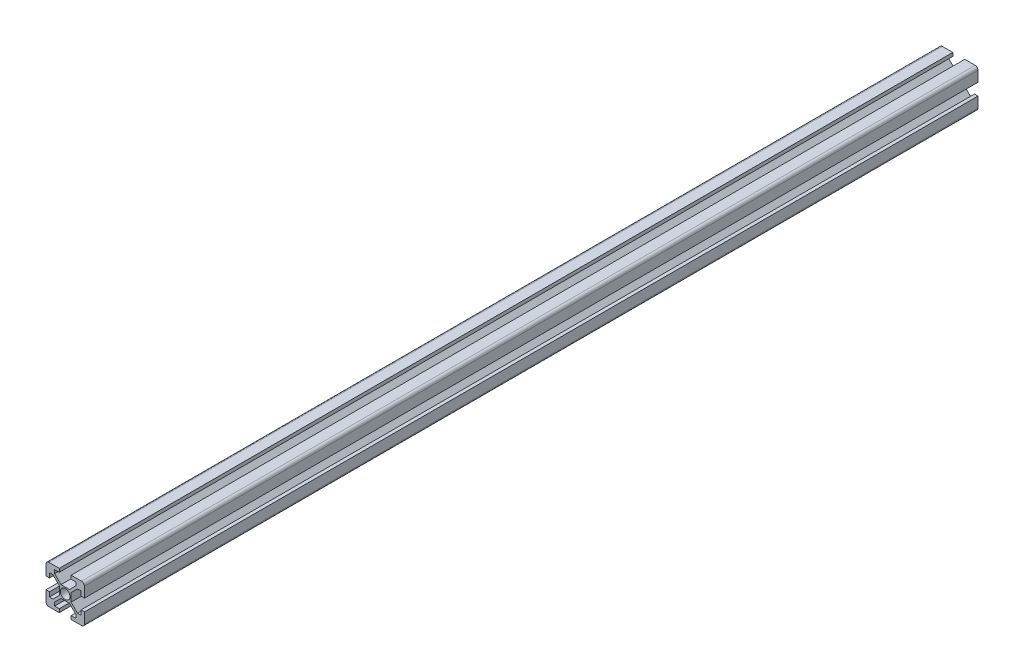
SolidWorks part; units mm, degrees
ref_plane "前视基准面" through (0, 0, 0) normal (0, 0, 1) x (1, 0, 0)
ref_plane "上视基准面" through (0, 0, 0) normal (0, 1, 0) x (1, 0, 0)
ref_plane "右视基准面" through (0, 0, 0) normal (1, 0, 0) x (0, 0, -1)
sketch "草图1" plane through (0, 0, 0) normal (0, 0, 1) x (1, 0, 0)
  line L0 (-10, -3.1) -> (-8.2, -3.1)
  line L1 (-8.5, 10) -> (8.5, 10)
  line L2 (-10, 8.5) -> (-10, -8.5)
  line L3 (-8.5, -10) -> (8.5, -10)
  line L4 (10, 8.5) -> (10, -8.5)
  line L5 (-10, 10) -> (10, -10) construction
  line L6 (-10, -10) -> (10, 10) construction
  line L7 (-3.0541, 3.1) -> (3.0541, 3.1)
  line L8 (-3.0541, 3.1) -> (-3.0541, -3.1)
  line L9 (-3.0541, -3.1) -> (3.0541, -3.1)
  line L10 (3.0541, 3.1) -> (3.0541, -3.1)
  line L11 (-3.0541, 3.1) -> (3.0541, -3.1) construction
  line L12 (-3.0541, -3.1) -> (3.0541, 3.1) construction
  line L13 (-8.2, -3.1) -> (-8.2, -5.5)
  line L14 (-8.2, -5.5) -> (-6.3971, -5.5)
  line L15 (-6.3971, -5.5) -> (-3.0541, -2.1571)
  line L16 (-5.5, 6.3971) -> (-2.1571, 3.0541)
  line L17 (-5.5, 8.2) -> (-5.5, 6.3971)
  line L18 (-3.1, 8.2) -> (-5.5, 8.2)
  line L19 (-3.1, 10) -> (-3.1, 8.2)
  line L20 (6.3971, 5.5) -> (3.0541, 2.1571)
  line L21 (8.2, 5.5) -> (6.3971, 5.5)
  line L22 (8.2, 3.1) -> (8.2, 5.5)
  line L23 (10, 3.1) -> (8.2, 3.1)
  line L24 (5.5, -6.3971) -> (2.1571, -3.0541)
  line L25 (5.5, -8.2) -> (5.5, -6.3971)
  line L26 (3.1, -8.2) -> (5.5, -8.2)
  line L27 (3.1, -10) -> (3.1, -8.2)
  line L28 (-3.1, -10) -> (-3.1, -8.2)
  line L29 (-3.1, -8.2) -> (-5.5, -8.2)
  line L30 (-5.5, -8.2) -> (-5.5, -6.3971)
  line L31 (-5.5, -6.3971) -> (-2.1571, -3.0541)
  line L32 (-8.2, 5.5) -> (-6.3971, 5.5)
  line L33 (-6.3971, 5.5) -> (-3.0541, 2.1571)
  line L34 (-8.2, 3.1) -> (-8.2, 5.5)
  line L35 (-10, 3.1) -> (-8.2, 3.1)
  line L36 (5.5, 8.2) -> (5.5, 6.3971)
  line L37 (5.5, 6.3971) -> (2.1571, 3.0541)
  line L38 (3.1, 8.2) -> (5.5, 8.2)
  line L39 (3.1, 10) -> (3.1, 8.2)
  line L40 (8.2, -5.5) -> (6.3971, -5.5)
  line L41 (6.3971, -5.5) -> (3.0541, -2.1571)
  line L42 (8.2, -3.1) -> (8.2, -5.5)
  line L43 (10, -3.1) -> (8.2, -3.1)
  circle A0 centre (0, 0) radius 2.5
  arc A1 (-10, 8.5) -> (-8.5, 10) centre (-8.5, 8.5) cw
  arc A2 (-10, -8.5) -> (-8.5, -10) centre (-8.5, -8.5) ccw
  arc A3 (8.5, 10) -> (10, 8.5) centre (8.5, 8.5) cw
  arc A4 (10, -8.5) -> (8.5, -10) centre (8.5, -8.5) cw
  point P0 (0, 0)
  point P20 (0, 0)
  point P26 (0, 0)
  point P32 (0, 0)
  point P38 (0, 0)
  point P60 (0, 0)
  dimension "D1" = 4
  dimension "D3" = 1.5
  dimension "D4" = 1.5
  dimension "D5" = 1.5
  dimension "D2" = 4
extrude "凸台-拉伸1" add sketch "草图1" along normal blind 465
